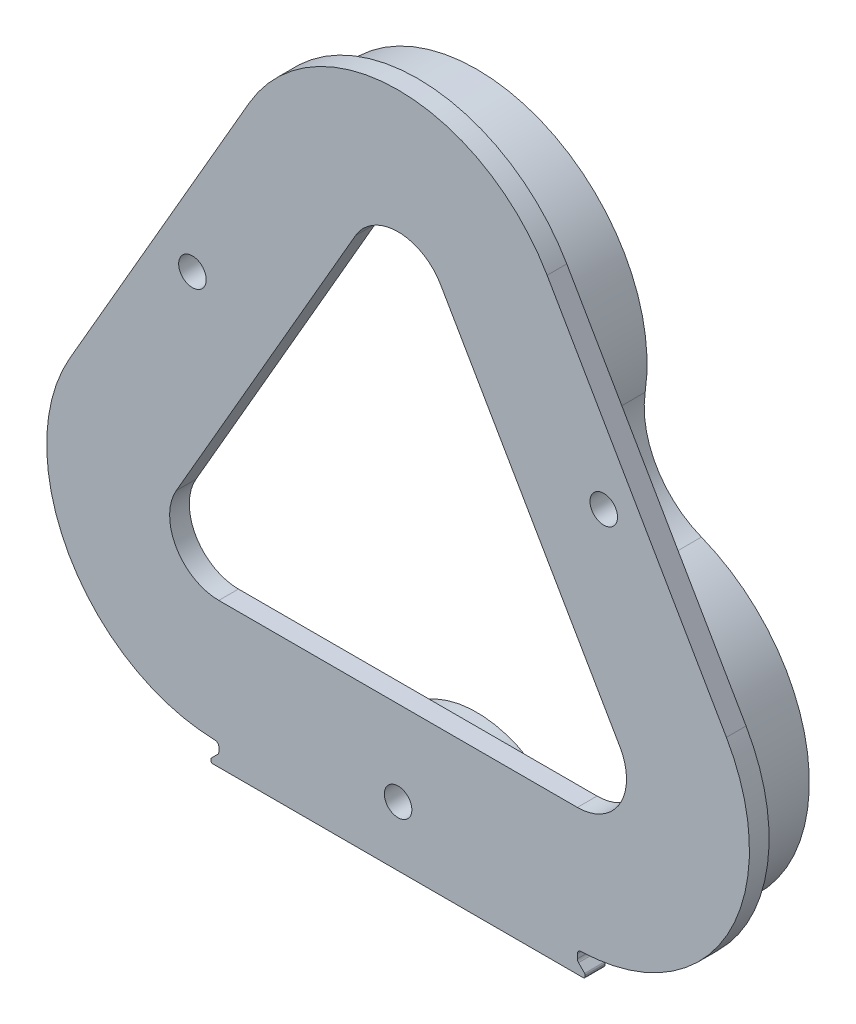
SolidWorks part; units mm, degrees
ref_plane "Front Plane" through (0, 0, 0) normal (0, 0, 1) x (1, 0, 0)
ref_plane "Top Plane" through (0, 0, 0) normal (0, 1, 0) x (1, 0, 0)
ref_plane "Right Plane" through (0, 0, 0) normal (1, 0, 0) x (0, 0, -1)
sketch "Sketch1" plane through (0, 0, 0) normal (0, 0, 1) x (1, 0, 0)
  line L1 (26.8468, 10.5) -> (63.3109, 10.5) construction
  line L2 (67.641, 18) -> (49.409, 49.5788) construction
  line L3 (26.7296, -3.1172) -> (26.1054, -3.7414)
  line L4 (78.4663, 24.25) -> (60.2343, 55.8288)
  line L5 (29.9234, 55.8288) -> (11.6913, 24.25)
  line L7 (78.4663, 24.25) -> (60.2343, 55.8288)
  line L8 (29.9234, 55.8288) -> (11.6913, 24.25)
  line L9 (40.7487, 49.5788) -> (22.5167, 18) construction
  line L10 (26.8468, 10.5) -> (63.3109, 10.5)
  line L11 (67.641, 18) -> (49.409, 49.5788)
  line L12 (40.7487, 49.5788) -> (22.5167, 18)
  line L31 (26.7296, -3.1172) -> (26.1054, -3.7414)
  line L32 (26.0468, -3.8828) -> (26.0468, -4)
  line L33 (26.0468, -3.8828) -> (26.0468, -4)
  line L34 (26.2468, -4.2) -> (63.9109, -4.2)
  line L35 (26.2468, -4.2) -> (63.9109, -4.2)
  line L36 (64.1109, -4) -> (64.1109, -3.8828)
  line L37 (64.1109, -4) -> (64.1109, -3.8828)
  line L38 (64.0523, -3.7414) -> (63.428, -3.1172)
  line L39 (64.0523, -3.7414) -> (63.428, -3.1172)
  line L40 (63.3109, -2.8343) -> (63.3109, -2.3955)
  line L41 (63.3109, -2.8343) -> (63.3109, -2.3955)
  line L42 (26.8468, -2.3955) -> (26.8468, -2.8343)
  line L43 (26.8468, -2.3955) -> (26.8468, -2.8343)
  arc A3 (63.702, -1.9956) -> (78.4663, 24.25) centre (63.3109, 15.5) ccw
  arc A4 (60.2343, 55.8288) -> (29.9234, 55.8288) centre (45.0788, 47.0788) ccw
  arc A5 (11.6913, 24.25) -> (26.4557, -1.9956) centre (26.8468, 15.5) ccw
  arc A6 (63.702, -1.9956) -> (78.4663, 24.25) centre (63.3109, 15.5) ccw
  arc A7 (60.2343, 55.8288) -> (29.9234, 55.8288) centre (45.0788, 47.0788) ccw
  arc A8 (11.6913, 24.25) -> (26.4557, -1.9956) centre (26.8468, 15.5) ccw
  circle A9 centre (65.9945, 38.1019) radius 1.4
  circle A10 centre (45.0788, 1.875) radius 1.4
  circle A11 centre (24.1632, 38.1019) radius 1.4
  arc A12 (22.5167, 18) -> (26.8468, 10.5) centre (26.8468, 15.5) ccw construction
  arc A13 (63.3109, 10.5) -> (67.641, 18) centre (63.3109, 15.5) ccw construction
  arc A14 (49.409, 49.5788) -> (40.7487, 49.5788) centre (45.0788, 47.0788) ccw construction
  arc A15 (63.3109, 10.5) -> (67.641, 18) centre (63.3109, 15.5) ccw
  arc A16 (49.409, 49.5788) -> (40.7487, 49.5788) centre (45.0788, 47.0788) ccw
  arc A17 (22.5167, 18) -> (26.8468, 10.5) centre (26.8468, 15.5) ccw
  arc A40 (26.1054, -3.7414) -> (26.0468, -3.8828) centre (26.2468, -3.8828) ccw
  arc A41 (26.1054, -3.7414) -> (26.0468, -3.8828) centre (26.2468, -3.8828) ccw
  arc A42 (26.0468, -4) -> (26.2468, -4.2) centre (26.2468, -4) ccw
  arc A43 (26.0468, -4) -> (26.2468, -4.2) centre (26.2468, -4) ccw
  arc A44 (63.9109, -4.2) -> (64.1109, -4) centre (63.9109, -4) ccw
  arc A45 (63.9109, -4.2) -> (64.1109, -4) centre (63.9109, -4) ccw
  arc A46 (64.1109, -3.8828) -> (64.0523, -3.7414) centre (63.9109, -3.8828) ccw
  arc A47 (64.1109, -3.8828) -> (64.0523, -3.7414) centre (63.9109, -3.8828) ccw
  arc A48 (63.3109, -2.8343) -> (63.428, -3.1172) centre (63.7109, -2.8343) ccw
  arc A49 (63.3109, -2.8343) -> (63.428, -3.1172) centre (63.7109, -2.8343) ccw
  arc A50 (63.702, -1.9956) -> (63.3109, -2.3955) centre (63.7109, -2.3955) ccw
  arc A51 (63.702, -1.9956) -> (63.3109, -2.3955) centre (63.7109, -2.3955) ccw
  arc A52 (26.8468, -2.3955) -> (26.4557, -1.9956) centre (26.4468, -2.3955) ccw
  arc A53 (26.8468, -2.3955) -> (26.4557, -1.9956) centre (26.4468, -2.3955) ccw
  arc A54 (26.7296, -3.1172) -> (26.8468, -2.8343) centre (26.4468, -2.8343) ccw
  arc A55 (26.7296, -3.1172) -> (26.8468, -2.8343) centre (26.4468, -2.8343) ccw
  point P7 (0, 0)
  point P12 (0, 0)
  point P14 (0, 0)
  dimension "D2" = 2.8
  dimension "D1" = 0
extrude "Boss-Extrude1" add sketch "Sketch1" along normal blind 2
sketch "Sketch2" plane through (0, 0, 0) normal (0, 0, -1) x (-1, 0, 0)
  arc A0 (-67.6236, 31.8529) -> (-61.3972, 42.6373) centre (-71.2871, 41.1576) ccw construction
  arc A1 (-67.6236, 31.8529) -> (-51.3053, 3.5886) centre (-61.5788, 16.5) ccw construction
  arc A2 (-38.8524, 3.5886) -> (-51.3053, 3.5886) centre (-45.0788, -4.2364) ccw construction
  arc A3 (-38.8524, 3.5886) -> (-22.5341, 31.8529) centre (-28.5788, 16.5) ccw construction
  arc A4 (-28.7605, 42.6373) -> (-22.5341, 31.8529) centre (-18.8706, 41.1576) ccw construction
  arc A5 (-28.7605, 42.6373) -> (-61.3972, 42.6373) centre (-45.0788, 45.0788) ccw construction
  arc A6 (-67.6236, 31.8529) -> (-61.3972, 42.6373) centre (-71.2871, 41.1576) ccw
  arc A7 (-67.6236, 31.8529) -> (-51.3053, 3.5886) centre (-61.5788, 16.5) ccw
  arc A8 (-38.8524, 3.5886) -> (-51.3053, 3.5886) centre (-45.0788, -4.2364) ccw
  arc A9 (-38.8524, 3.5886) -> (-22.5341, 31.8529) centre (-28.5788, 16.5) ccw
  arc A10 (-28.7605, 42.6373) -> (-22.5341, 31.8529) centre (-18.8706, 41.1576) ccw
  arc A11 (-28.7605, 42.6373) -> (-61.3972, 42.6373) centre (-45.0788, 45.0788) ccw
  arc A15 (-27.9495, 42.516) -> (-62.2082, 42.516) centre (-45.0788, 45.0788) ccw
  arc A16 (-67.924, 32.6159) -> (-62.2082, 42.516) centre (-71.2871, 41.1576) ccw
  arc A17 (-67.924, 32.6159) -> (-50.7947, 2.947) centre (-61.5788, 16.5) ccw
  arc A18 (-39.363, 2.947) -> (-50.7947, 2.947) centre (-45.0788, -4.2364) ccw
  arc A19 (-39.363, 2.947) -> (-22.2336, 32.6159) centre (-28.5788, 16.5) ccw
  arc A20 (-27.9495, 42.516) -> (-22.2336, 32.6159) centre (-18.8706, 41.1576) ccw
  dimension "D1" = 0.82
extrude "Boss-Extrude2" add sketch "Sketch2" along normal blind 6
